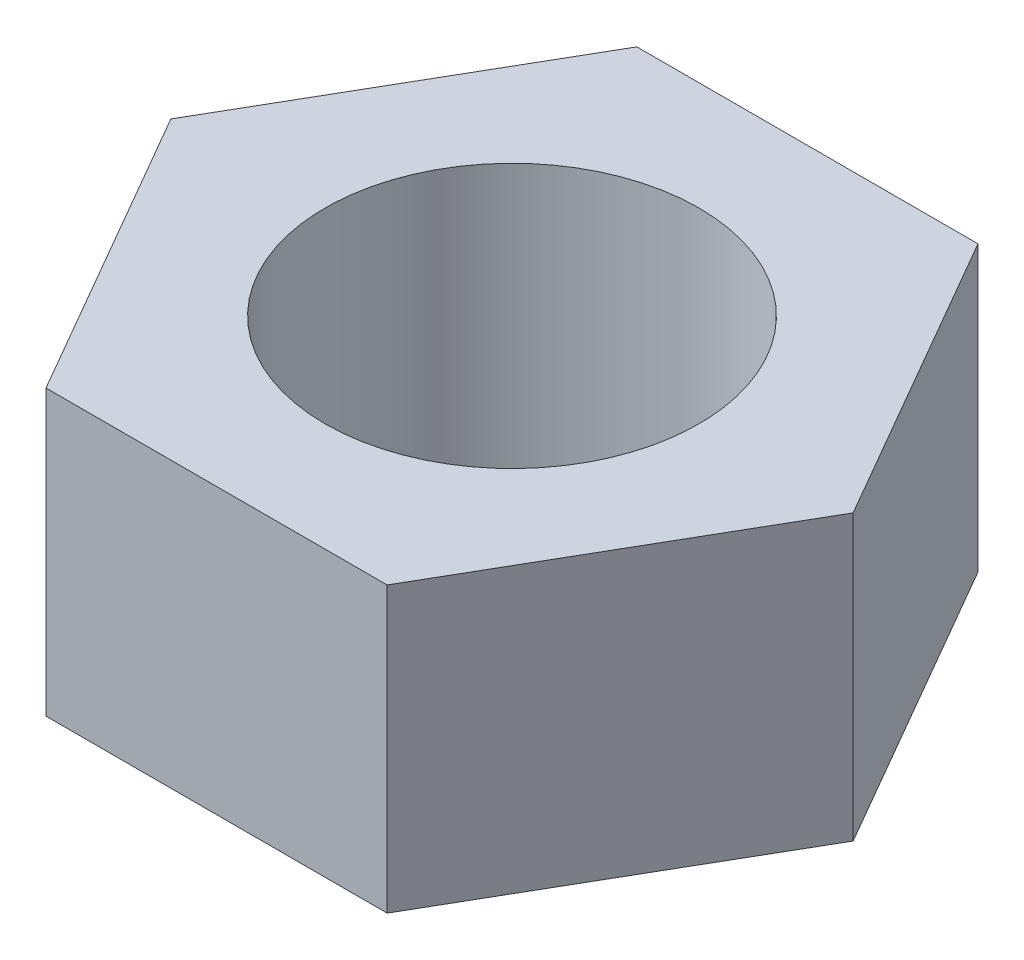
SolidWorks part; units mm, degrees
ref_plane "Front" through (0, 0, 0) normal (0, 0, 1) x (1, 0, 0)
ref_plane "Top" through (0, 0, 0) normal (0, 1, 0) x (1, 0, 0)
ref_plane "Right" through (0, 0, 0) normal (1, 0, 0) x (0, 0, -1)
sketch "Эскиз1" plane through (0, 0, 0) normal (0, 1, 0) x (1, 0, 0)
  line L1 (2.2805, -3.95) -> (4.5611, 0)
  line L2 (4.5611, 0) -> (2.2805, 3.95)
  line L3 (2.2805, 3.95) -> (-2.2805, 3.95)
  line L4 (-2.2805, 3.95) -> (-4.5611, 0)
  line L5 (-4.5611, 0) -> (-2.2805, -3.95)
  line L6 (-2.2805, -3.95) -> (2.2805, -3.95)
  circle A0 centre (0, 0) radius 3.95 construction
  circle A1 centre (0, 0) radius 2.5
  dimension "D1" = 5
  dimension "D2" = 7.9
extrude "Бобышка-Вытянуть1" add sketch "Эскиз1" along normal blind 3.8
